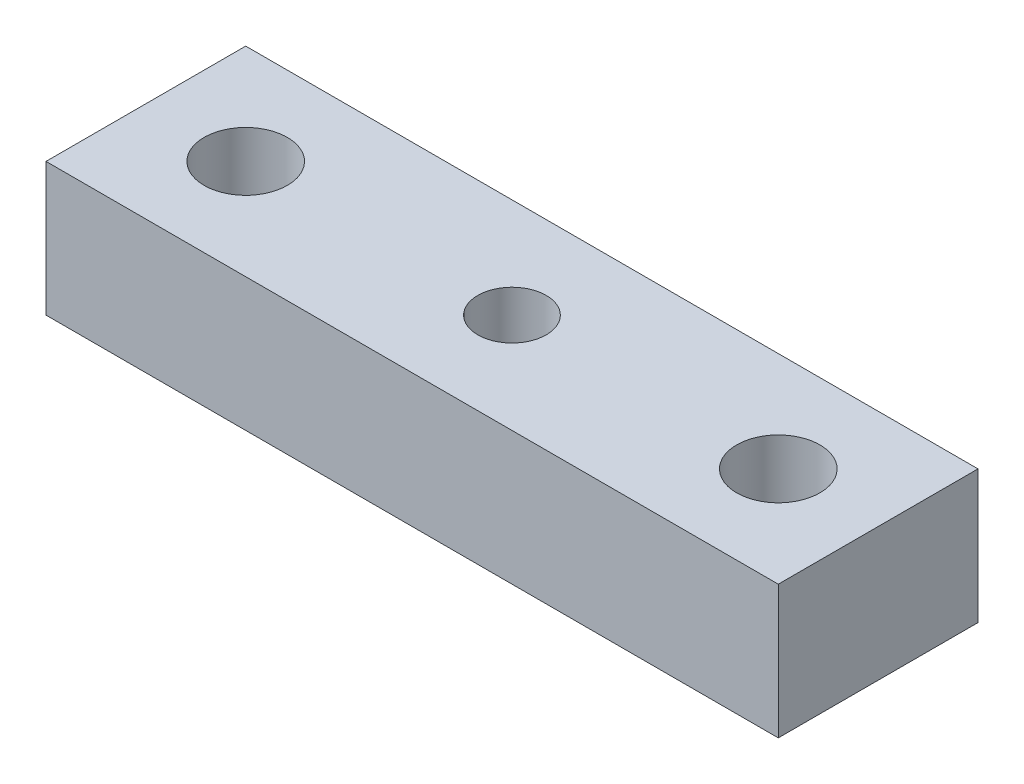
SolidWorks part; units mm, degrees
material "6061-T6 (SS)"
ref_plane "Front" through (0, 0, 0) normal (0, 0, 1) x (1, 0, 0)
ref_plane "Top" through (0, 0, 0) normal (0, 1, 0) x (1, 0, 0)
ref_plane "Right" through (0, 0, 0) normal (1, 0, 0) x (0, 0, -1)
sketch "Sketch1" plane through (0, 0, 0) normal (0, 0, 1) x (1, 0, 0)
  line L1 (-34.925, -6.35) -> (34.925, -6.35)
  line L2 (-34.925, -6.35) -> (-34.925, 6.35)
  line L3 (-34.925, 6.35) -> (34.925, 6.35)
  line L4 (34.925, -6.35) -> (34.925, 6.35)
  line L5 (-34.925, -6.35) -> (34.925, 6.35) construction
  line L6 (-34.925, 6.35) -> (34.925, -6.35) construction
  point P0 (0, 0)
  dimension "D1" = 69.85
  dimension "D2" = 12.7
extrude "Boss-Extrude1" add sketch "Sketch1" along normal blind 19.05
sketch "Sketch5" plane through (0, 6.35, 0) normal (0, 1, 0) x (1, 0, 0)
  line L0 (34.925, -9.525) -> (25.4, -9.525) construction
  line L1 (34.925, -19.05) -> (34.925, 0) construction
  line L2 (-25.4, -9.525) -> (0, -9.525) construction
  line L3 (-25.4, -9.525) -> (-34.925, -9.525) construction
  line L4 (-34.925, -19.05) -> (-34.925, 0) construction
  line L5 (0, -9.525) -> (25.4, -9.525) construction
  dimension "D1" = 50.8
hole_wizard "5/16 (0.3125) Diameter Hole1" positions "Sketch7" profile "Sketch6" hole size "5/16" standard "ANSI Inch" end condition through all
sketch "Sketch7" plane through (0, 6.35, 0) normal (0, 1, 0) x (1, 0, 0)
  point P0 (-25.4, -9.525)
  point P3 (25.4, -9.525)
sketch "Sketch6" plane through (-25.4, 6.35, 9.525) normal (1, 0, 0) x (0, 0, 1)
  line L0 (0, 0) -> (0, 12.7)
  line L1 (0, 12.7) -> (3.9687, 12.7)
  line L2 (3.9687, 12.7) -> (3.9687, 0)
  line L5 (3.9687, 0) -> (0, 0)
  line L11 (0, -6.35) -> (0, 107.95) construction
  dimension "Thru Hole Dia." = 7.9375
  dimension "Thru Hole Depth" = 12.7
hole_wizard "5/16-18 Tapped Hole1" positions "Sketch9" profile "Sketch8" tap size "5/16-18" standard "ANSI Inch" end condition through all
sketch "Sketch9" plane through (0, 6.35, 0) normal (0, 1, 0) x (1, 0, 0)
  point P0 (0, -9.525)
sketch "Sketch8" plane through (0, 6.35, 9.525) normal (1, 0, 0) x (0, 0, 1)
  line L0 (0, 0) -> (0, 12.7)
  line L1 (0, 12.7) -> (3.2639, 12.7)
  line L2 (3.2639, 12.7) -> (3.2639, 0)
  line L5 (3.2639, 0) -> (0, 0)
  line L11 (0, -6.35) -> (0, 107.95) construction
  dimension "Thru Tap Drill Dia." = 6.5278
  dimension "Thru Tap Drill Depth" = 12.7
cosmetic thread "Hole Thread1"
